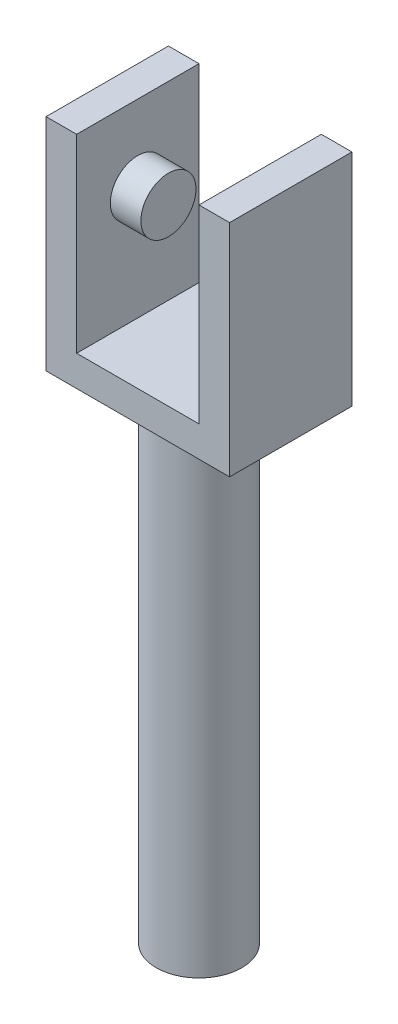
SolidWorks part; units mm, degrees
other "Markup1"
sketch "Sketch7" plane through (75, 490, 50) normal (0.0513, 0.2225, 0.9736) x (0.9846, -0.1746, -0.012)
ref_plane "Front Plane" through (0, 0, 0) normal (0, 0, 1) x (1, 0, 0)
ref_plane "Top Plane" through (0, 0, 0) normal (0, 1, 0) x (1, 0, 0)
ref_plane "Right Plane" through (0, 0, 0) normal (1, 0, 0) x (0, 0, -1)
sketch "Sketch1" plane through (0, 0, 0) normal (0, 1, 0) x (1, 0, 0)
  circle A0 centre (0, 0) radius 35
  dimension "D1" = 70
extrude "Boss-Extrude1" add sketch "Sketch1" along normal blind 392.5
sketch "Sketch2" plane through (0, 392.5, 0) normal (0, 1, 0) x (1, 0, 0)
  line L1 (-75, 50) -> (75, 50)
  line L2 (-75, 50) -> (-75, -50)
  line L3 (-75, -50) -> (75, -50)
  line L4 (75, 50) -> (75, -50)
  line L5 (-75, 50) -> (75, -50) construction
  line L6 (-75, -50) -> (75, 50) construction
  point P0 (0, 0)
  dimension "D1" = 100
  dimension "D2" = 150
extrude "Boss-Extrude2" add sketch "Sketch2" along normal blind 180
sketch "Sketch3" plane through (0, 0, 50) normal (0, 0, 1) x (1, 0, 0)
  line L0 (-50, 572.5) -> (-50, 447.5)
  line L1 (-75, 572.5) -> (75, 572.5) construction
  line L2 (-50, 447.5) -> (50, 447.5)
  line L3 (50, 447.5) -> (50, 572.5)
  line L4 (-50, 572.5) -> (50, 572.5)
  line L5 (-75, 572.5) -> (-75, 392.5) construction
  line L6 (75, 572.5) -> (75, 392.5) construction
  line L7 (-75, 392.5) -> (75, 392.5) construction
  dimension "D1" = 25
  dimension "D2" = 25
  dimension "D3" = 100
  dimension "D4" = 125
  dimension "D5" = 55
extrude "Cut-Extrude1" cut sketch "Sketch3" against normal blind 150
sketch "Sketch4" plane through (50, 0, 0) normal (-1, 0, 0) x (0, 0, 1)
  line L0 (0, 572.5) -> (0, 447.5) construction
  line L1 (50, 572.5) -> (-50, 572.5) construction
  line L2 (-50, 447.5) -> (50, 447.5) construction
  line L3 (50, 510) -> (-50, 510) construction
  line L4 (50, 447.5) -> (50, 572.5) construction
  line L5 (-50, 447.5) -> (-50, 572.5) construction
  circle A0 centre (0, 510) radius 22.5
  dimension "D1" = 45
extrude "Boss-Extrude3" add sketch "Sketch4" along normal blind 25
sketch "Sketch5" plane through (-50, 0, 0) normal (1, 0, 0) x (0, 0, -1)
  line L0 (0, 572.5) -> (0, 447.5) construction
  line L1 (50, 572.5) -> (-50, 572.5) construction
  line L2 (50, 447.5) -> (-50, 447.5) construction
  line L3 (50, 510) -> (-50, 510) construction
  line L4 (50, 572.5) -> (50, 447.5) construction
  line L5 (-50, 572.5) -> (-50, 447.5) construction
  circle A0 centre (0, 510) radius 22.5
  dimension "D1" = 45
extrude "Boss-Extrude4" add sketch "Sketch5" along normal blind 25
sketch "Sketch6" plane through (0, 0, 50) normal (0, 0, 1) x (1, 0, 0)
  line L1 (-50, 447.5) -> (50, 447.5)
  line L2 (-50, 447.5) -> (-50, 417.5)
  line L3 (-50, 417.5) -> (50, 417.5)
  line L4 (50, 447.5) -> (50, 417.5)
  dimension "D1" = 100
  dimension "D2" = 30
extrude "Cut-Extrude2" cut sketch "Sketch6" against normal through all
ref_point "Point2"
ref_point "Point5"
